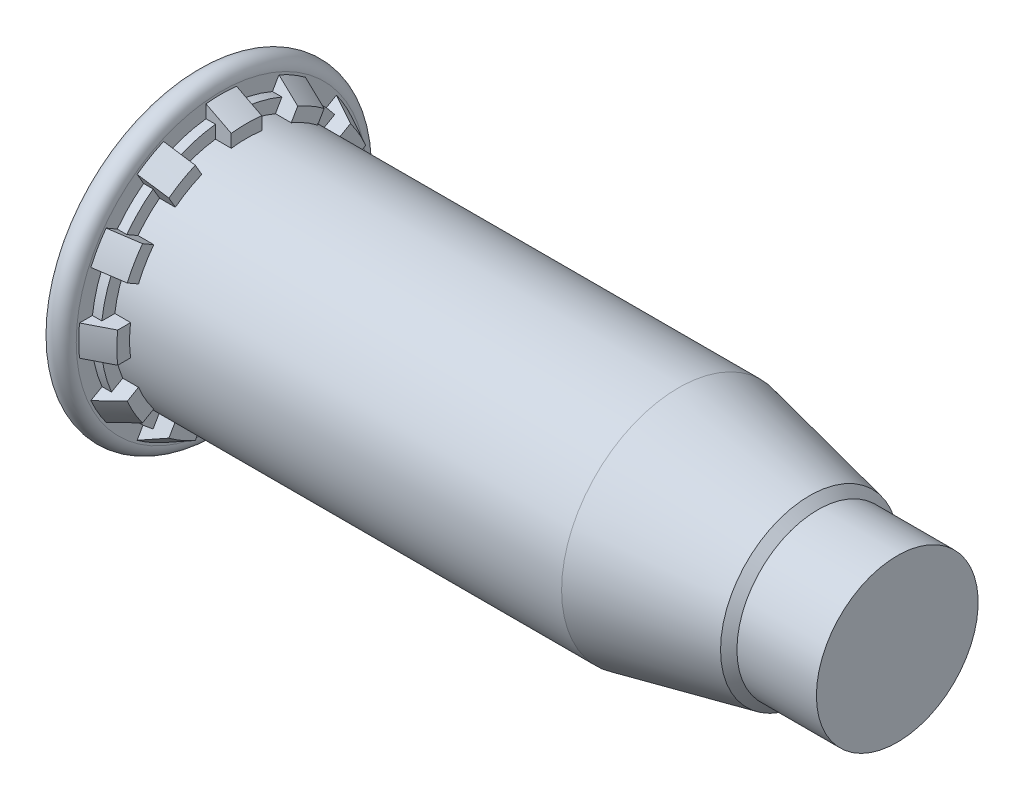
SolidWorks part; units mm, degrees
revolve "BaseBody" add sketch "BodySke" angle 360 about L6
sketch "BodySke" plane through (0, 0, 0) normal (0, 0, 1) x (1, 0, 0)
  line L0 (0, 0) -> (0, 3.9345)
  line L1 (0.6858, 3.9395) -> (0.6858, 3.8735)
  line L2 (0.6858, 3.8735) -> (1.3716, 3.5242)
  line L3 (1.3716, 3.175) -> (13.1064, 3.175)
  line L5 (19.05, 0) -> (0, 0)
  line L6 (0, 0) -> (50.554, 0) construction
  line L7 (1.3716, 3.5242) -> (1.3716, 3.175)
  line L8 (16.6688, 2.4193) -> (13.1064, 3.175)
  line L9 (-9.525, 4.2799) -> (9.525, 4.2799) construction
  line L11 (2.6416, 19.05) -> (2.6416, -3.175) construction
  line L12 (19.05, 2.1971) -> (19.05, 0)
  line L13 (9.525, -4.2799) -> (-9.525, -4.2799) construction
  line L14 (0.0051, 3.9395) -> (0.0051, 3.9345)
  line L15 (0, 3.9345) -> (0.0051, 3.9345)
  line L16 (16.891, 2.1971) -> (19.05, 2.1971)
  line L17 (16.6688, 2.4193) -> (16.891, 2.1971)
  arc A0 (0.0051, 3.9395) -> (0.6858, 3.9395) centre (0.3454, 3.9395) cw
  dimension "H_dia" = 8.5598
  dimension "Shoulder_lower_dia" = 7.747
  dimension "Shoulder_upper_dia" = 7.0485
  dimension "D1" = 0.0051
  dimension "D2" = 0.0051
  dimension "Shoulder_ht" = 1.3716
  dimension "Advance" = 1.27
  dimension "Minor_dia" = 4.8387
  dimension "Diameter" = 6.35
  dimension "T_dim" = 0.6858
  dimension "Length" = 19.05
  dimension "Dog_dia" = 4.3942
  dimension "Dog_len" = 2.159
  dimension "D5" = 45
  dimension "Thread_trans" = 3.7846
cosmetic thread "ThreadCosmetic" [suppressed] parameters "Thread_length"=13.2398, "Thread_minor"=4.8387
extrude "RibCut1" cut sketch "RibCut1Ske" against normal blind 0.4286
sketch "RibCut1Ske" plane through (1.3716, 0, 0) normal (1, 0, 0) x (0, 0, -1)
  line L0 (0.4144, 3.1478) -> (0.4144, 4.2598)
  line L1 (1.215, 2.9333) -> (1.771, 3.8963)
  line L2 (0, 0) -> (0, 4.9784) construction
  line L3 (0, 0) -> (0.4144, 3.1478) construction
  line L4 (0, 0) -> (1.215, 2.9333) construction
  arc A1 (1.215, 2.9333) -> (0.4144, 3.1478) centre (0, 0) ccw
  arc A2 (1.771, 3.8963) -> (0.4144, 4.2598) centre (0, 0) ccw
  dimension "Angle" = 30
  dimension "Inner_dia" = 6.35
  dimension "Outer_dia" = 8.5598
  dimension "Rib_root_half_angle" = 7.5
  dimension "Rib_root_gap_angle" = 15
ref_plane "Plane1" through (0, 0, 0) normal (0, 0, 1) x (1, 0, 0)
ref_plane "Plane2" through (0, 0, 0) normal (0, 1, 0) x (1, 0, 0)
ref_plane "Plane3" through (0, 0, 0) normal (1, 0, 0) x (0, 0, -1)
sketch "ThdSchSke" plane through (0, 0, 0) normal (0, 0, 1) x (1, 0, 0)
  line L0 (3.429, -2.4193) -> (2.8999, -3.175)
  line L1 (3.429, -2.4193) -> (3.9581, -3.175)
  line L2 (3.9581, -3.175) -> (3.9581, -3.9688)
  line L3 (-3.175, 0) -> (5.1513, 0) construction
  line L5 (3.9581, -3.9688) -> (2.8999, -3.9688)
  line L6 (2.8999, -3.9688) -> (2.8999, -3.175)
  line L7 (0, 3.9345) -> (0, -3.9345) construction
  dimension "Diameter" = 6.35
  dimension "SideAngle" = 55
  dimension "VeeAngle" = 70
  dimension "Thread_minor" = 4.8387
  dimension "Overcut" = 7.9375
  dimension "Start" = 3.429
revolve "ThreadSchematic" [suppressed] cut sketch "ThdSchSke" angle 360 about L3
pattern_linear "ThdSchPat" [suppressed]
sketch "RibCut2Ske" plane through (1.3716, 0, 0) normal (1, 0, 0) x (0, 0, -1)
  line L0 (0.4144, 3.4998) -> (0.4144, 4.2598)
  line L1 (1.391, 3.2381) -> (1.771, 3.8963)
  line L2 (0.4144, 3.1478) -> (0.4144, 4.9596) construction
  line L3 (0, 0) -> (0, 5.0239) construction
  line L4 (0, 0) -> (0.4144, 3.1478) construction
  line L5 (0, 0) -> (1.215, 2.9333) construction
  line L6 (1.215, 2.9333) -> (2.1244, 4.5085) construction
  arc A1 (1.391, 3.2381) -> (0.4144, 3.4998) centre (0, 0) ccw
  arc A2 (1.771, 3.8963) -> (0.4144, 4.2598) centre (0, 0) ccw
  circle A4 centre (0, 0) radius 3.175 construction
  dimension "Angle" = 30
  dimension "Outer_dia" = 8.5598
  dimension "Rib_root_half_angle" = 7.5
  dimension "Rib_root_gap_angle" = 15
extrude "RibCut2" cut sketch "RibCut2Ske" against normal blind 0.6858
pattern_circular "RibCutsPat" count 12 every 30 about axis through (0, 0, 0) along (1, 0, 0) of "RibCut2", "RibCut1"
equation "' \"Length@BodySke\" = 0.75"
equation "' \"H_dia@BodySke\" = 0.337"
equation "' \"Start@ThdSchSke\" = 0.135"
equation "' \"Dog_dia@BodySke\" = 0.173"
equation "' \"Dog_len@BodySke\" = 0.085"
equation "' \"Thread_trans@BodySke\" = 0.149"
equation "' \"Diameter@BodySke\" = 0.25"
equation "' \"Minor_dia@BodySke\" =0.1905"
equation "' \"Minor_dia@BodySke\" = 0.1905"
equation "' \"Advance@BodySke\" = 0.05"
equation "\"T_dim@BodySke\" = \"Start@ThdSchSke\" * 0.2"
equation "\"Shoulder_ht@BodySke\" = \"Start@ThdSchSke\" * 0.4"
equation "\"Shoulder_lower_dia@BodySke\" = \"H_dia@BodySke\" - \"Start@ThdSchSke\" * 0.2 - .005"
equation "\"Shoulder_upper_dia@BodySke\" = ( \"Shoulder_lower_dia@BodySke\" + \"Diameter@BodySke\" ) /2"
equation "\"Num_ribs@RibCutsPat\" = 12"
equation "\"Angle@RibCutsPat\" = 360 / \"Num_ribs@RibCutsPat\""
equation "\"Angle@RibCut1Ske\" =\"Angle@RibCutsPat\""
equation "\"Rib_root_half_angle@RibCut1Ske\" = \"Angle@RibCut1Ske\" / 4"
equation "\"Rib_root_gap_angle@RibCut1Ske\" = \"Angle@RibCut1Ske\" - (2 * \"Rib_root_half_angle@RibCut1Ske\" )"
equation "\"Inner_dia@RibCut1Ske\" = \"Diameter@BodySke\""
equation "\"Outer_dia@RibCut1Ske\" = \"H_dia@BodySke\""
equation "\"Depth@RibCut1\" =  \"Start@ThdSchSke\" * 0.125"
equation "\"Angle@RibCut2Ske\" =\"Angle@RibCutsPat\""
equation "\"Rib_root_half_angle@RibCut2Ske\" = \"Angle@RibCut1Ske\" / 4"
equation "\"Rib_root_gap_angle@RibCut2Ske\" = \"Angle@RibCut1Ske\" - (2 * \"Rib_root_half_angle@RibCut1Ske\" )"
equation "\"Rib_root_dia@RibCut2Ske\" = \"Diameter@BodySke\""
equation "\"Inner_dia@RibCut2Ske\" = \"Shoulder_upper_dia@BodySke\""
equation "\"Outer_dia@RibCut2Ske\" = \"H_dia@BodySke\""
equation "\"Depth@RibCut2\" =  \"Start@ThdSchSke\" * 0.2"
equation "\"Thread_length@ThreadCosmetic\" = \"Length@BodySke\" - \"Start@ThdSchSke\"  - \"Dog_len@BodySke\"  - ( \"Minor_dia@BodySke\" - \"Dog_dia@BodySke\" ) / 2"
equation "\"Thread_minor@ThreadCosmetic\" = \"Minor_dia@BodySke\""
equation "\"Thread_minor@ThdSchSke\" = \"Minor_dia@BodySke\""
equation "\"Diameter@ThdSchSke\" = \"Diameter@BodySke\""
equation "\"Overcut@ThdSchSke\" = \"Diameter@BodySke\" * 1.25"
equation "\"Num_threads@ThdSchPat\" = int( \"Thread_length@ThreadCosmetic\" / \"Advance@BodySke\" + 0.999 )  + 1"
equation "\"Advance@ThdSchPat\" = \"Thread_length@ThreadCosmetic\" /  (\"Num_threads@ThdSchPat\" - 1) 'relax it"
equation "\"Num_threads@ThdSchPat\" = \"Num_threads@ThdSchPat\" - sgn( \"Num_threads@ThdSchPat\" - 1) '---chamfered tips only---"
